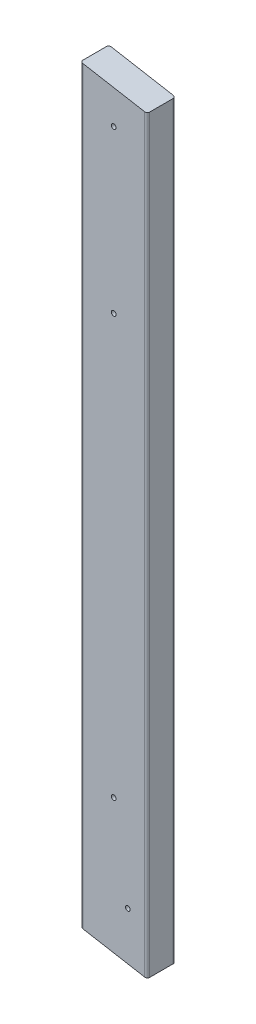
SolidWorks part; units mm, degrees
ref_plane "Front" through (0, 0, 0) normal (0, 0, 1) x (1, 0, 0)
ref_plane "Top" through (0, 0, 0) normal (0, 1, 0) x (1, 0, 0)
ref_plane "Right" through (0, 0, 0) normal (1, 0, 0) x (0, 0, -1)
sketch "Sketch1" plane through (0, 0, 0) normal (0, 1, 0) x (1, 0, 0)
  line L1 (44.45, 19.05) -> (-44.45, 19.05)
  line L2 (44.45, 19.05) -> (44.45, -19.05)
  line L3 (44.45, -19.05) -> (-44.45, -19.05)
  line L4 (-44.45, 19.05) -> (-44.45, -19.05)
  line L5 (44.45, 19.05) -> (-44.45, -19.05) construction
  line L6 (44.45, -19.05) -> (-44.45, 19.05) construction
  point P0 (0, 0)
  dimension "D1" = 88.9
  dimension "D2" = 38.1
extrude "Boss-Extrude1" add sketch "Sketch1" along normal blind 1016
sketch "Sketch2" plane through (0, 0, 19.05) normal (0, 0, 1) x (1, 0, 0)
  line L0 (44.45, 0) -> (-44.45, 0)
  line L1 (-44.45, 0) -> (-44.45, 15.6755)
  line L2 (-44.45, 1016) -> (-44.45, 0) construction
  line L3 (-44.45, 15.6755) -> (44.45, 0)
  line L4 (-44.45, 1016) -> (44.45, 1000.3245)
  line L5 (44.45, 1016) -> (44.45, 0) construction
  line L6 (44.45, 1000.3245) -> (44.45, 1016)
  line L7 (44.45, 1016) -> (-44.45, 1016)
  dimension "D1" = 10
extrude "Cut-Extrude1" cut sketch "Sketch2" against normal through all
hole_wizard "1/4 (0.25) Diameter Hole1" positions "Sketch4" profile "Sketch5" hole size "1/4" standard "ANSI Inch" end condition through all
sketch "Sketch4" plane through (0, 0, 19.05) normal (0, 0, 1) x (1, 0, 0)
  line L1 (-44.45, 1016) -> (-44.45, 15.6755) construction
  point P0 (18.787, 68.7376)
  point P3 (0, 187.401)
  point P6 (0, 747.1266)
  point P9 (0, 963.0266)
  dimension "D1" = 44.45
  dimension "D2" = 63.237
  dimension "D3" = 52.9734
  dimension "D4" = 268.8734
  dimension "D5" = 828.599
  dimension "D6" = 947.2624
sketch "Sketch5" plane through (18.787, 68.7376, 19.05) normal (1, 0, 0) x (0, -1, 0)
  line L0 (0, 0) -> (0, 38.1)
  line L1 (0, 38.1) -> (3.175, 38.1)
  line L2 (3.175, 38.1) -> (3.175, 0)
  line L5 (3.175, 0) -> (0, 0)
  line L11 (0, -6.35) -> (0, 107.95) construction
  dimension "Thru Hole Dia." = 6.35
  dimension "Thru Hole Depth" = 38.1
fillet "Fillet1" radius 3.175 4 edges at (44.45, 500.1623, -19.05) (44.45, 500.1623, 19.05) (-44.45, 515.8377, -19.05) (-44.45, 515.8377, 19.05)
